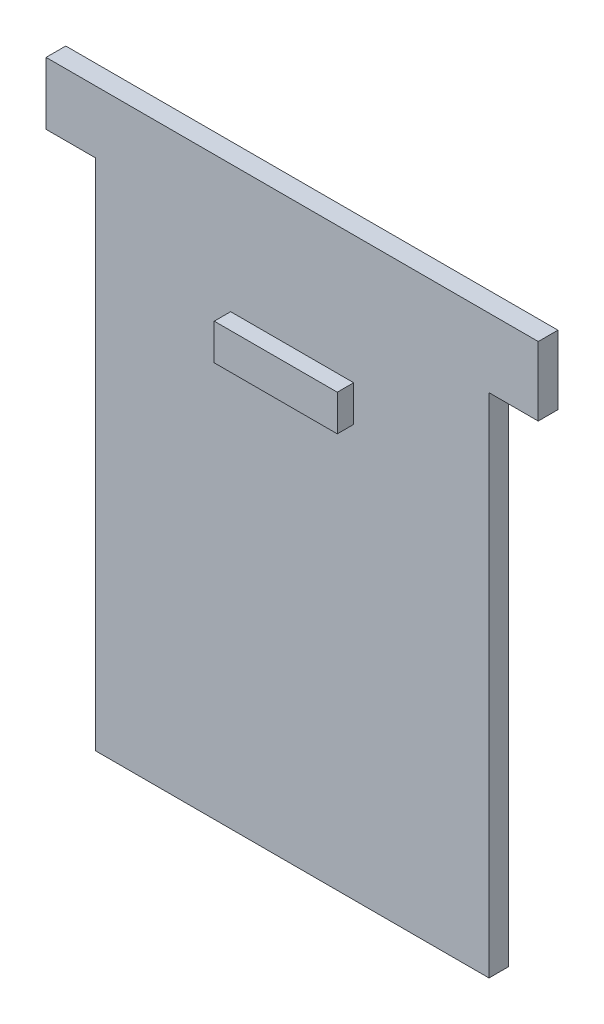
SolidWorks part; units mm, degrees
ref_plane "Front Plane" through (0, 0, 0) normal (0, 0, 1) x (1, 0, 0)
ref_plane "Top Plane" through (0, 0, 0) normal (0, 1, 0) x (1, 0, 0)
ref_plane "Right Plane" through (0, 0, 0) normal (1, 0, 0) x (0, 0, -1)
sketch "Sketch1" plane through (0, 0, 0) normal (0, 0, 1) x (1, 0, 0)
  line L0 (0, 0) -> (300, 0)
  line L1 (300, 0) -> (300, -42)
  line L2 (300, -42) -> (270, -42)
  line L3 (270, -42) -> (270, -351)
  line L4 (270, -351) -> (30, -351)
  line L5 (30, -351) -> (30, -38)
  line L6 (30, -38) -> (0, -38)
  line L7 (0, -38) -> (0, 0)
  dimension "D1" = 42
  dimension "D2" = 30
  dimension "D3" = 30
  dimension "D4" = 300
  dimension "D5" = 313
  dimension "D9" = 240
extrude "Boss-Extrude1" add sketch "Sketch1" along normal blind 12
sketch "Sketch2" plane through (0, 0, 12) normal (0, 0, 1) x (1, 0, 0)
  line L0 (270, -351) -> (270, -42) construction
  line L1 (112.5, -78) -> (187.5, -78)
  line L2 (112.5, -78) -> (112.5, -100)
  line L3 (112.5, -100) -> (187.5, -100)
  line L4 (187.5, -78) -> (187.5, -100)
  line L5 (300, 0) -> (0, 0) construction
  line L6 (30, -38) -> (30, -351) construction
  dimension "D1" = 82.5
  dimension "D2" = 78
  dimension "D3" = 100
  dimension "D4" = 82.5
extrude "Boss-Extrude2" add sketch "Sketch2" along normal blind 10
